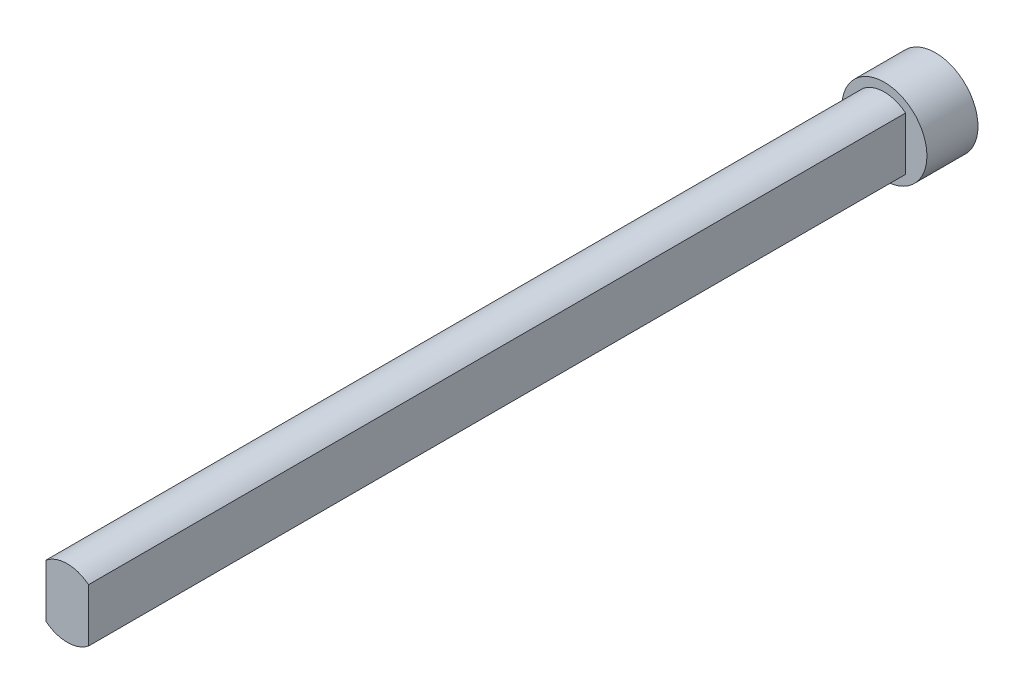
SolidWorks part; units mm, degrees
ref_plane "Front Plane" through (0, 0, 0) normal (0, 0, 1) x (1, 0, 0)
ref_plane "Top Plane" through (0, 0, 0) normal (0, 1, 0) x (1, 0, 0)
ref_plane "Right Plane" through (0, 0, 0) normal (1, 0, 0) x (0, 0, -1)
sketch "Sketch1" plane through (0, 0, 0) normal (0, 0, 1) x (1, 0, 0)
  circle A0 centre (0, 0) radius 5
  dimension "D1" = 10
extrude "Boss-Extrude1" add sketch "Sketch1" along normal blind 6
sketch "Sketch2" plane through (0, 0, 6) normal (0, 0, 1) x (1, 0, 0)
  circle A0 centre (0, 0) radius 4
  dimension "D1" = 8
extrude "Boss-Extrude2" add sketch "Sketch2" along normal blind 96
cosmetic thread "Cosmetic Thread2" parameters "D1"=50, "D2"=6.891
sketch "Sketch6" plane through (0, 0, 102) normal (0, 0, 1) x (1, 0, 0)
  line L1 (-2.5, 8.2155) -> (2.5, 8.2155)
  line L2 (-2.5, 8.2155) -> (-2.5, -8.2155)
  line L3 (-2.5, -8.2155) -> (2.5, -8.2155)
  line L4 (2.5, 8.2155) -> (2.5, -8.2155)
  line L5 (-2.5, 8.2155) -> (2.5, -8.2155) construction
  line L6 (-2.5, -8.2155) -> (2.5, 8.2155) construction
  point P0 (0, 0)
  dimension "D1" = 5
extrude "Cut-Extrude1" cut sketch "Sketch6" against normal up to surface (96 mm away) flip side to cut up to face at (4, 0, 6)
